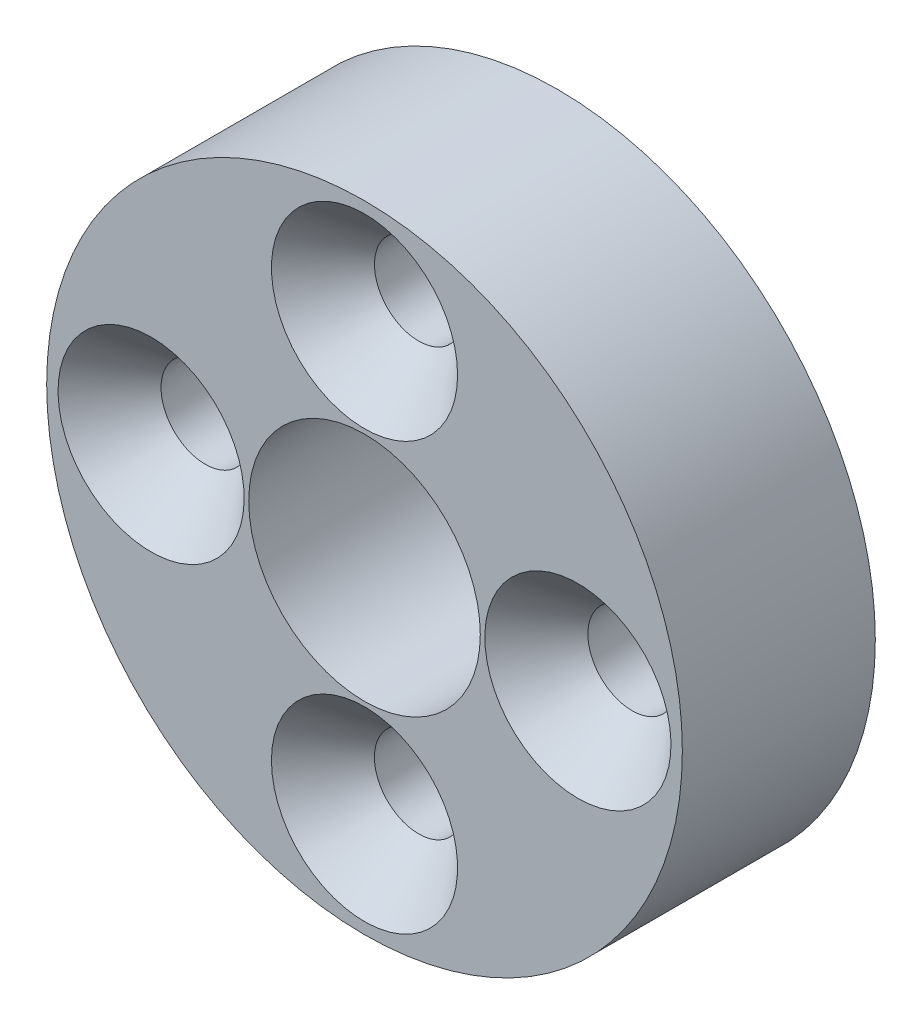
SolidWorks part; units mm, degrees
material "1060 Alloy"
ref_plane "Front Plane" through (0, 0, 0) normal (0, 0, 1) x (1, 0, 0)
ref_plane "Top Plane" through (0, 0, 0) normal (0, 1, 0) x (1, 0, 0)
ref_plane "Right Plane" through (0, 0, 0) normal (1, 0, 0) x (0, 0, -1)
sketch "Sketch1" plane through (0, 0, 0) normal (0, 0, 1) x (1, 0, 0)
  line L0 (0, 11.938) -> (0, 0) construction
  line L5 (0, 0) -> (11.938, 0) construction
  line L6 (0, -11.938) -> (0, 0) construction
  line L7 (0, 0) -> (-11.938, 0) construction
  circle A0 centre (0, 0) radius 17.78
  circle A1 centre (-11.938, 0) radius 2.4765
  circle A2 centre (0, -11.938) radius 2.4765
  circle A3 centre (11.938, 0) radius 2.4765
  circle A4 centre (0, 11.938) radius 2.4765
  circle A5 centre (0, 0) radius 6.477
  dimension "D1" = 35.56
  dimension "D4" = 4.953
  dimension "D2" = 12.954
  dimension "D3" = 11.938
extrude "Boss-Extrude1" add sketch "Sketch1" along normal blind 10.795
sketch "Sketch2" plane through (0, 0, 0) normal (0, 0, -1) x (-1, 0, 0)
  line L1 (-8.255, -8.255) -> (8.255, -8.255)
  line L2 (-8.255, -8.255) -> (-8.255, 8.255)
  line L3 (-8.255, 8.255) -> (8.255, 8.255)
  line L4 (8.255, -8.255) -> (8.255, 8.255)
  line L5 (-8.255, -8.255) -> (8.255, 8.255) construction
  line L6 (-8.255, 8.255) -> (8.255, -8.255) construction
  circle A0 centre (0, 0) radius 6.477 construction
  circle A1 centre (0, 0) radius 6.477
  point P0 (0, 0)
  dimension "D1" = 16.51
extrude "Boss-Extrude2" add sketch "Sketch2" along normal blind 3.175
sketch "Sketch5" plane through (0, 0, 0) normal (1, 0, 0) x (0, 0, -1)
  line L0 (-10.795, 11.938) -> (0, 11.938) construction
  line L1 (-10.795, 14.4145) -> (-10.795, 9.4615) construction
  line L2 (0, 9.4615) -> (0, 14.4145) construction
  line L3 (-10.795, 11.938) -> (-10.795, 17.145)
  line L4 (-10.795, 17.78) -> (-10.795, -17.78) construction
  line L5 (-10.795, 17.145) -> (-7.493, 14.1719)
  line L6 (-7.493, 14.1719) -> (-7.493, 11.938)
  line L7 (-7.493, 11.938) -> (-10.795, 11.938)
  dimension "D1" = 42
  dimension "D2" = 5.207
  dimension "D3" = 3.302
revolve "Cut-Revolve1" cut sketch "Sketch5" angle 360 about L0
pattern_circular "CirPattern4" count 4 over 360 about axis through (0, 0, 0) along (0, 0, 1) of "Cut-Revolve1"
